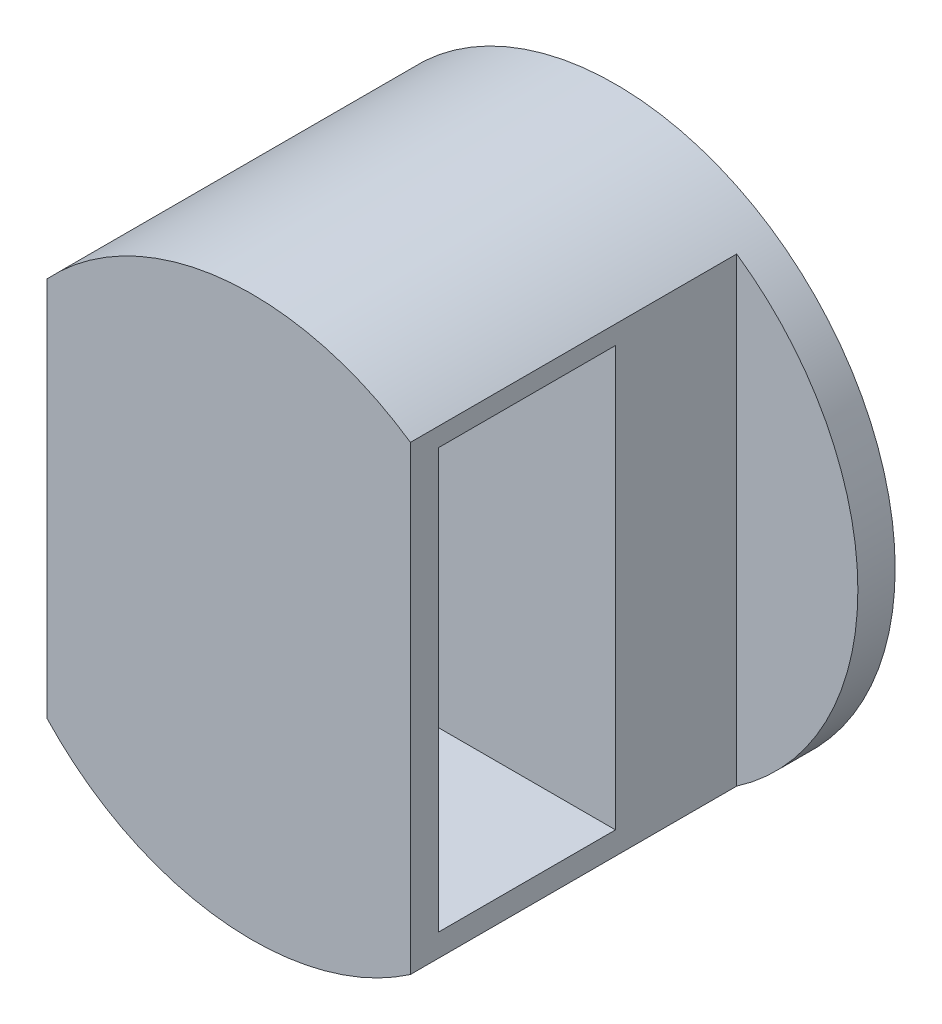
SolidWorks part; units mm, degrees
ref_plane "Plan de face" through (0, 0, 0) normal (0, 0, 1) x (1, 0, 0)
ref_plane "Plan de dessus" through (0, 0, 0) normal (0, 1, 0) x (1, 0, 0)
ref_plane "Plan de droite" through (0, 0, 0) normal (1, 0, 0) x (0, 0, -1)
sketch "Esquisse1" plane through (0, 0, 0) normal (0, 0, 1) x (1, 0, 0)
  circle A0 centre (-21.6771, 21.4883) radius 30
extrude "Boss.-Extru.1" add sketch "Esquisse1" along normal blind 4
sketch "Esquisse4" plane through (0, 0, 4) normal (0, 0, 1) x (1, 0, 0)
  line L3 (-43.6771, 21.4883) -> (-43.6771, 1.0922)
  line L4 (-43.6771, 1.0922) -> (-43.6771, 41.8844)
  line L5 (-4.6771, -3.2301) -> (-4.6771, 46.2067)
  circle A0 centre (-21.6771, 21.4883) radius 30 construction
  arc A1 (-43.6771, 41.8844) -> (-4.6771, 46.2067) centre (-21.6771, 21.4883) cw
  arc A2 (-43.6771, 1.0922) -> (-4.6771, -3.2301) centre (-21.6771, 21.4883) ccw
  point P7 (-4.6771, 21.4883)
  circle M1 centre (-21.6771, 21.4883) radius 30
extrude "Boss.-Extru.3" add sketch "Esquisse4" along normal blind 35 contours L5 L4 L3 M1
sketch "Esquisse7" plane through (-4.6771, 0, 0) normal (1, 0, 0) x (0, 0, -1)
  line L0 (-39, 46.2067) -> (-4, 46.2067) construction
  line L1 (-36, 44.2067) -> (-17, 44.2067)
  line L2 (-36, 44.2067) -> (-36, -0.7933)
  line L3 (-36, -0.7933) -> (-17, -0.7933)
  line L4 (-17, 44.2067) -> (-17, -0.7933)
  line L5 (-4, -3.2301) -> (-4, 46.2067) construction
  dimension "D1" = 45
  dimension "D2" = 2
  dimension "D3" = 19
  dimension "D4" = 13
extrude "Enlèv. mat.-Extru.1" cut sketch "Esquisse7" against normal blind 30
sketch "Esquisse8" plane through (0, 0, 0) normal (0, 0, -1) x (-1, 0, 0)
  circle A1 centre (21.6771, 21.4883) radius 1.0012
  point P5 (21.6771, 21.4883)
extrude "Enlèv. mat.-Extru.2" cut sketch "Esquisse8" against normal blind 2
